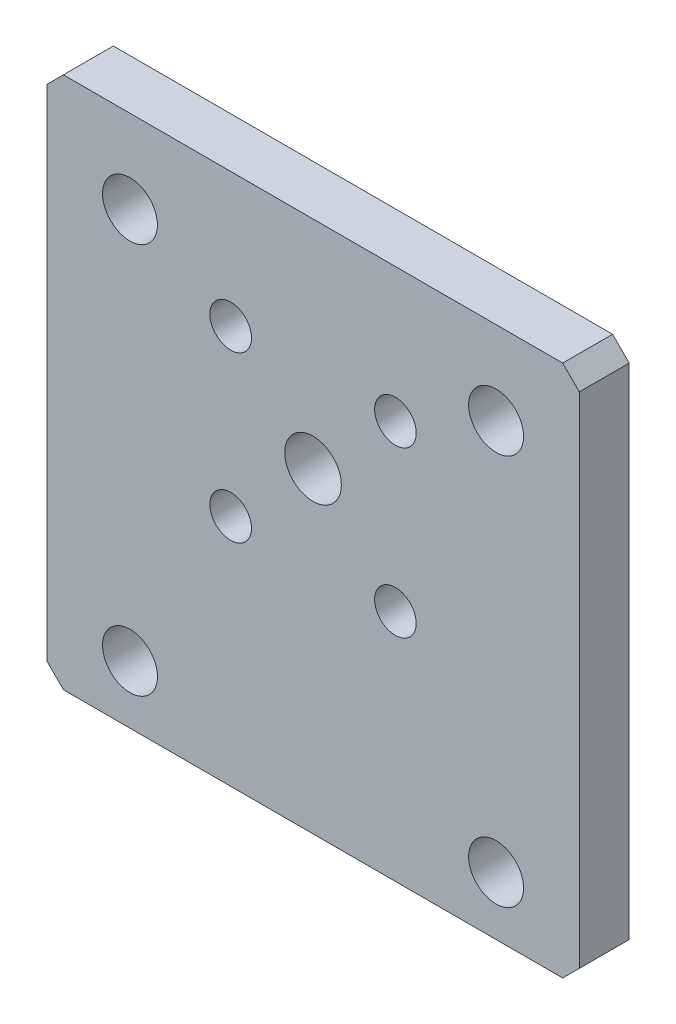
SolidWorks part; units mm, degrees
material "Q235"
ref_plane "前视基准面" through (0, 0, 0) normal (0, 0, 1) x (1, 0, 0)
ref_plane "上视基准面" through (0, 0, 0) normal (0, 1, 0) x (1, 0, 0)
ref_plane "右视基准面" through (0, 0, 0) normal (1, 0, 0) x (0, 0, -1)
sketch "草图1" plane through (0, 0, 0) normal (0, 0, 1) x (1, 0, 0)
  line L0 (0, 13) -> (0, -19) construction
  line L1 (16, 13) -> (-16, 13)
  line L2 (16, 13) -> (16, -19)
  line L3 (16, -19) -> (-16, -19)
  line L4 (-16, 13) -> (-16, -19)
  line L5 (16, 13) -> (-16, -19) construction
  line L6 (16, -19) -> (-16, 13) construction
  point P0 (0, 0)
  dimension "D1" = 32
  dimension "D2" = 32
  dimension "D3" = 13
extrude "凸台-拉伸1" add sketch "草图1" along normal blind 3
hole_wizard "Ø3.4 (3.4) 直径孔1" positions "草图3" profile "草图2" hole size "Ø3.4" standard "Gb"
sketch "草图3" plane through (0, 0, 3) normal (0, 0, 1) x (1, 0, 0)
  point P0 (0, 0)
sketch "草图2" plane through (0, 0, 3) normal (1, 0, 0) x (0, -1, 0)
  line L0 (0, 0) -> (0, 7.0215)
  line L1 (0, 7.0215) -> (1.7, 6)
  line L2 (1.7, 6) -> (1.7, 0)
  line L5 (1.7, 0) -> (0, 0)
  line L10 (0, 7.0215) -> (-1.7, 6) construction
  line L11 (0, -6.35) -> (0, 107.95) construction
  dimension "孔直径" = 3.4
  dimension "孔深度" = 6
  dimension "导头角度" = 118
hole_wizard "M3 螺纹孔1" positions "草图5" profile "草图4" tap size "M3" standard "Gb"
sketch "草图5" plane through (0, 0, 3) normal (0, 0, 1) x (1, 0, 0)
  line L6 (-4.9497, -4.9497) -> (0, 0) construction
  line L7 (0, 0) -> (-8.1472, 0) construction
  circle A0 centre (0, 0) radius 7 construction
  point P4 (-4.9497, -4.9497)
  dimension "D1" = 14
  dimension "D2" = 45
sketch "草图4" plane through (-4.9497, -4.9497, 3) normal (1, 0, 0) x (0, -1, 0)
  line L0 (0, 0) -> (0, 9.2511)
  line L1 (0, 9.2511) -> (1.25, 8.5)
  line L2 (1.25, 8.5) -> (1.25, 0)
  line L5 (1.25, 0) -> (0, 0)
  line L10 (0, 9.2511) -> (-1.25, 8.5) construction
  line L11 (0, -6.35) -> (0, 107.95) construction
  dimension "螺纹孔钻头直径" = 2.5
  dimension "螺纹孔钻头深度" = 8.5
  dimension "导头角度" = 118
cosmetic thread "孔螺蚊线2" parameters "D1"=4, "D2"=3
pattern_circular "阵列(圆周)1" count 4 over 360 about axis through (0, 0, 0) along (0, 0, 1) of "M3 螺纹孔1"
hole_wizard "M4 螺纹孔1" positions "草图7" profile "草图6" tap size "M4" standard "Gb" end condition up to next
sketch "草图7" plane through (0, 0, 3) normal (0, 0, 1) x (1, 0, 0)
  line L0 (0, 0) -> (0, 12.2252) construction
  line L3 (-11, 8) -> (11, 8) construction
  line L4 (11, 8) -> (11, -15.5) construction
  line L5 (11, -15.5) -> (-11, -15.5) construction
  line L6 (-11, -15.5) -> (-11, 8) construction
  line L10 (-16, -19) -> (16, -19) construction
  circle A0 centre (0, 0) radius 1.7 construction
  point P0 (-11, 8)
  point P2 (11, 8)
  point P5 (-11, -15.5)
  point P7 (11, -15.5)
  dimension "D1" = 8
  dimension "D2" = 22
  dimension "D3" = 3.5
cosmetic thread "孔螺蚊线3" parameters "D2"=4
cosmetic thread "孔螺蚊线4" parameters "D2"=4
sketch "草图6" plane through (-11, 8, 3) normal (1, 0, 0) x (0, -1, 0)
  line L0 (0, 0) -> (0, 3)
  line L1 (0, 3) -> (1.65, 3)
  line L2 (1.65, 3) -> (1.65, 0)
  line L5 (1.65, 0) -> (0, 0)
  line L11 (0, -6.35) -> (0, 107.95) construction
  dimension "通孔螺纹孔钻头直径" = 3.3
  dimension "通孔螺纹孔钻头深度" = 3
cosmetic thread "孔螺蚊线5" parameters "D2"=4
cosmetic thread "孔螺蚊线6" parameters "D2"=4
chamfer "倒角1" distance 1 angle 45 4 edges at (-16, -19, 1.5) (16, -19, 1.5) (16, 13, 1.5) (-16, 13, 1.5)
